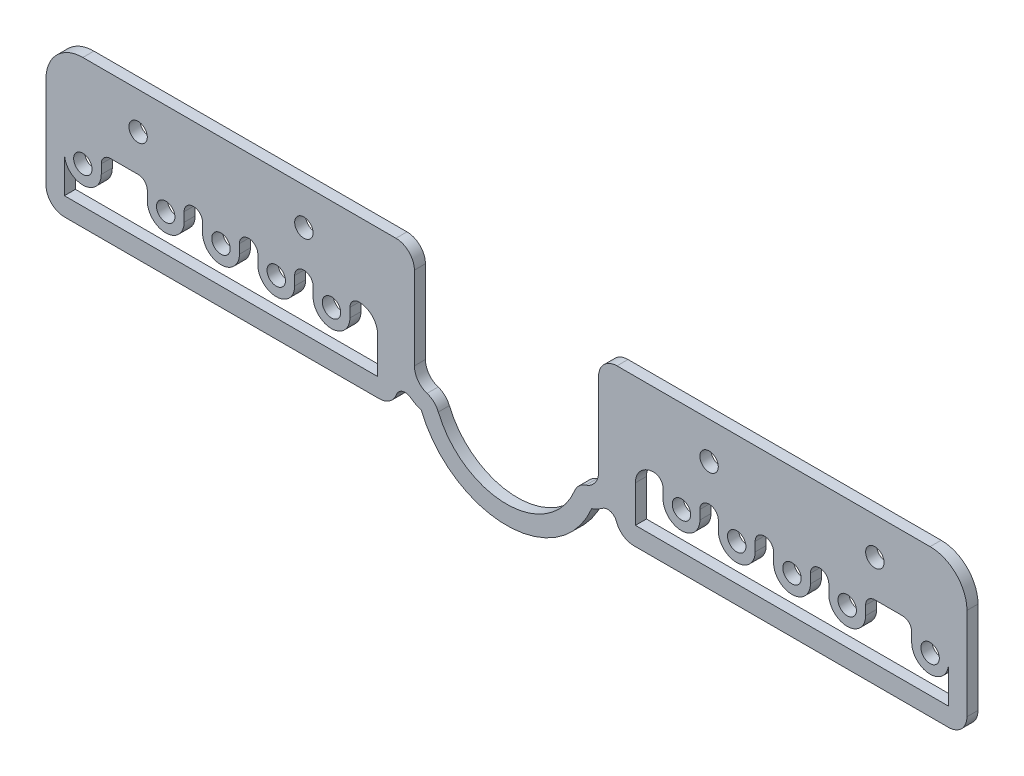
SolidWorks part; units mm, degrees
ref_plane "Front Plane" through (0, 0, 0) normal (0, 0, 1) x (1, 0, 0)
ref_plane "Top Plane" through (0, 0, 0) normal (0, 1, 0) x (1, 0, 0)
ref_plane "Right Plane" through (0, 0, 0) normal (1, 0, 0) x (0, 0, -1)
sketch "Sketch1" plane through (0, 0, 0) normal (0, 0, 1) x (1, 0, 0)
  line L0 (-40, 20) -> (-40, 55) construction
  line L4 (-250, -55) -> (-250, 3.1783)
  line L8 (-50, 75) -> (-230, 75) construction
  line L17 (0, -20) -> (0, -40)
  line L25 (0, -65) -> (0, -75)
  line L26 (0, 75) -> (0, -75) construction
  line L27 (-50, 95) -> (50, 95) construction
  line L34 (0, -75) -> (-230, -75)
  line L156 (-50, 75) -> (-230, 75) construction
  line L161 (0, -40) -> (0, -65)
  line L165 (-164.3309, 75) -> (-60, 75)
  line L167 (-230, 75) -> (-220, 75)
  line L171 (-250, 3.1783) -> (-250, 55)
  line L172 (-220, 75) -> (-164.3309, 75)
  line L173 (-50, 65) -> (-50, 20)
  arc A0 (-40, 20) -> (0, -20) centre (0, 20) ccw construction
  circle A1 centre (0, 20) radius 30 construction
  arc A4 (-230, -75) -> (-250, -55) centre (-230, -55) cw
  arc A5 (-250, 55) -> (-230, 75) centre (-230, 55) cw
  arc A124 (0, -20) -> (-37, 4.8013) centre (0, 20) cw
  arc A125 (-60, 75) -> (-50, 65) centre (-60, 65) cw
  arc A126 (-43.125, 10.5008) -> (-50, 20) centre (-40, 20) cw
  arc A127 (-37, 4.8013) -> (-43.125, 10.5008) centre (-46.25, 1.0016) ccw
  point P0 (0, 0)
  point P10 (-50, 10)
  point P11 (0, 50)
  point P30 (-40, 75)
  point P45 (0, -30)
  point P74 (0, 95)
  dimension "D3" = 80
  dimension "D4" = 60
  dimension "D6" = 55
  dimension "D7" = 75
  dimension "D10" = 10
  dimension "D11" = 20
  dimension "D8" = 10
  dimension "D5" = 10
  dimension "D9" = 20
  dimension "D13" = 210
  dimension "D16" = 100
  dimension "D17" = 20
  dimension "D26" = 250
extrude "Boss-Extrude1" add sketch "Sketch1" along normal blind 6
mirror "Mirror1" about plane through (0, -20, 6) normal (-1, 0, 0) of "Boss-Extrude1"
sketch "Sketch3" plane through (0, 0, 6) normal (0, 0, 1) x (1, 0, 0)
  line L3 (50, 20) -> (50, 65) construction
  line L4 (50, 20) -> (50, 65) construction
  line L7 (-60, 75) -> (-230, 75) construction
  line L8 (-250, 55) -> (-250, -55) construction
  line L9 (250, 55) -> (250, -55) construction
  circle A2 centre (110, 55) radius 5
  circle A3 centre (200, 55) radius 5
  circle A4 centre (-200, 55) radius 5
  circle A5 centre (-110, 55) radius 5
  dimension "D3" = 10
  dimension "D4" = 10
  dimension "D5" = 10
  dimension "D6" = 10
  dimension "D8" = 20
  dimension "D12" = 50
  dimension "D2" = 140
  dimension "D7" = 20
  dimension "D9" = 50
  dimension "D10" = 140
extrude "Cut-Extrude1" cut sketch "Sketch3" against normal through all contours A2 | A3 | A5 | A4
sketch "Sketch4" plane through (0, 0, 6) normal (0, 0, 1) x (1, 0, 0)
  line L0 (-230, -75) -> (230, -75) construction
  line L1 (-70, 25) -> (-70, -55)
  line L2 (-50, 20) -> (-50, 65) construction
  line L3 (-60, 75) -> (-230, 75) construction
  line L7 (-240, -55) -> (-240, 25)
  line L8 (-250, 55) -> (-250, -55) construction
  line L9 (-210, -65) -> (-190, -65)
  line L10 (-115, 25) -> (-115, 30)
  line L11 (-110, 35) -> (-80, 35)
  line L12 (-220, 25) -> (-220, 30)
  line L13 (-215, 35) -> (-140, 35)
  line L14 (-135, 30) -> (-135, 25)
  line L15 (-230, -65) -> (-210, -65)
  line L16 (-110, -65) -> (-90, -65)
  line L17 (0, 0) -> (0, -75) construction
  line L18 (-190, -65) -> (-110, -65)
  line L19 (90, -65) -> (80, -65)
  line L20 (190, -65) -> (110, -65)
  line L21 (-90, -65) -> (-80, -65)
  line L22 (110, -65) -> (90, -65)
  line L23 (230, -65) -> (210, -65)
  line L24 (230, 25) -> (125, 25) construction
  line L30 (221.3397, 20) -> (133.6603, 20)
  line L32 (110, 35) -> (80, 35)
  line L33 (115, 25) -> (115, 30)
  line L35 (210, -65) -> (190, -65)
  line L36 (240, -55) -> (240, 25)
  line L37 (70, 25) -> (70, -55)
  line L38 (125, 35) -> (230, 35)
  line L39 (230, 20) -> (125, 20) construction
  circle A0 centre (-230, 25) radius 5
  circle A3 centre (-125, 25) radius 5
  arc A6 (-230, -65) -> (-240, -55) centre (-230, -55) cw
  arc A8 (-222.2775, 18.6468) -> (-231.6408, 15.1355) centre (-230, 25) ccw
  arc A9 (-127.2754, 15.2623) -> (-127.1893, 15.2426) centre (-125, 25) ccw
  arc A12 (-110, 35) -> (-115, 30) centre (-110, 30) ccw
  arc A13 (-140, 35) -> (-135, 30) centre (-140, 30) cw
  arc A14 (-215, 35) -> (-220, 30) centre (-215, 30) ccw
  arc A15 (-70, -55) -> (-80, -65) centre (-80, -55) cw
  arc A16 (-70, 25) -> (-80, 35) centre (-80, 25) ccw
  arc A17 (-117.6445, 18.2253) -> (-134.5708, 22.1017) centre (-125, 25) ccw
  arc A19 (-231.6408, 15.1355) -> (-222.2775, 18.6468) centre (-230, 25) ccw
  arc A20 (-134.5708, 22.1017) -> (-117.3815, 18.5225) centre (-125, 25) ccw
  arc A21 (133.6603, 20) -> (117.3815, 18.5225) centre (125, 25) cw
  arc A22 (231.6408, 15.1355) -> (222.2775, 18.6468) centre (230, 25) cw
  arc A23 (117.6445, 18.2253) -> (125, 35) centre (125, 25) cw
  arc A24 (70, 25) -> (80, 35) centre (80, 25) cw
  arc A25 (70, -55) -> (80, -65) centre (80, -55) ccw
  arc A26 (230, 35) -> (231.6408, 15.1355) centre (230, 25) cw
  arc A28 (110, 35) -> (115, 30) centre (110, 30) cw
  arc A29 (127.2754, 15.2623) -> (127.1893, 15.2426) centre (125, 25) cw
  arc A30 (222.2775, 18.6468) -> (221.3397, 20) centre (230, 25) cw
  arc A31 (230, -65) -> (240, -55) centre (230, -55) ccw
  circle A32 centre (125, 25) radius 5
  circle A33 centre (230, 25) radius 5
  point P0 (0, -75)
  dimension "D1" = 10
  dimension "D13" = 10
  dimension "D14" = 20
  dimension "D10" = 5
  dimension "D15" = 5
  dimension "D17" = 10
  dimension "D2" = 230
  dimension "D4" = 5
  dimension "D5" = 125
  dimension "D8" = 50
  dimension "D9" = 10
  dimension "D11" = 20
  dimension "D12" = 80
  dimension "D16" = 80
extrude "Cut-Extrude2" cut sketch "Sketch4" against normal through all contours A20 A17 L14 A13 L13 A14 L12 A8 A19 L7 A6 L15 L9 L18 L16 L21 A15 L1 A16 L11 A12 L10 A9 | A0 | A3
sketch "Sketch8" plane through (0, 0, 6) normal (0, 0, 1) x (1, 0, 0)
  line L0 (-60, 0) -> (-60, -65)
  line L2 (-60, -65) -> (60, -65)
  line L3 (60, -65) -> (60, 0)
  line L4 (-230, -65) -> (-80, -65) construction
  arc A0 (43.125, 10.5008) -> (50, 20) centre (40, 20) ccw construction
  arc A1 (43.125, 10.5008) -> (37, 4.8013) centre (46.25, 1.0016) ccw construction
  arc A2 (-37, 4.8013) -> (-43.125, 10.5008) centre (-46.25, 1.0016) ccw construction
  arc A3 (-50, 20) -> (-43.125, 10.5008) centre (-40, 20) ccw construction
  arc A4 (-37, 4.8013) -> (37, 4.8013) centre (0, 20) ccw construction
  arc A5 (43.125, 10.5008) -> (50, 20) centre (40, 20) ccw construction
  arc A6 (43.125, 10.5008) -> (37, 4.8013) centre (46.25, 1.0016) ccw construction
  arc A7 (-37, 4.8013) -> (-43.125, 10.5008) centre (-46.25, 1.0016) ccw construction
  arc A8 (-50, 20) -> (-43.125, 10.5008) centre (-40, 20) ccw construction
  arc A9 (-37, 4.8013) -> (37, 4.8013) centre (0, 20) ccw construction
  arc A10 (-52, 4) -> (-46.25, 1.0016) centre (-40, 20) ccw
  arc A11 (-46.25, 1.0016) -> (-46.25, 1.0016) centre (-46.25, 1.0016) ccw
  arc A12 (-46.25, 1.0016) -> (46.25, 1.0016) centre (0, 20) ccw
  arc A13 (46.25, 1.0016) -> (46.25, 1.0016) centre (46.25, 1.0016) ccw
  arc A14 (46.25, 1.0016) -> (52, 4) centre (40, 20) ccw
  arc A15 (46.25, 1.0016) -> (60, 20) centre (40, 20) ccw construction
  arc A16 (60, 0) -> (52, 4) centre (55, 0) ccw
  arc A17 (-60, 20) -> (-46.25, 1.0016) centre (-40, 20) ccw construction
  arc A18 (-60, 0) -> (-52, 4) centre (-55, 0) cw
  dimension "D2" = 5
  dimension "D1" = 10
extrude "Cut-Extrude5" cut sketch "Sketch8" against normal through all
fillet "Fillet5" radius 5 1 edges at (-60, -65, 3)
fillet "Fillet6" radius 5 1 edges at (60, -65, 3)
mirror "Mirror2" about plane through (0, 0, 0) normal (1, 0, 0) of "Cut-Extrude2"
sketch "Sketch9" plane through (0, 0, 6) normal (0, 0, 1) x (1, 0, 0)
  line L0 (-250, 5) -> (-70, 5)
  line L1 (-250, 55) -> (-250, -55) construction
  line L2 (250, 55) -> (250, -55) construction
  line L3 (250, 5) -> (250, -5)
  line L4 (250, -5) -> (70, -5)
  line L5 (-250, -5) -> (-250, 5)
  line L6 (-215, 35) -> (-140, 35) construction
  line L7 (-70, 5) -> (-70, -5)
  line L8 (-70, 25) -> (-70, -55) construction
  line L9 (70, 5) -> (70, -5)
  line L10 (70, 25) -> (70, -55) construction
  line L11 (70, 5) -> (250, 5)
  line L12 (-70, -5) -> (-250, -5)
  dimension "D1" = 10
  dimension "D2" = 30
extrude "Boss-Extrude2" add sketch "Sketch9" against normal up to surface (6 mm away) up to face at (225, 25, 0)
sketch "Sketch10" plane through (0, 0, 6) normal (0, 0, 1) x (1, 0, 0)
  line L0 (-240, -5) -> (-250, -5)
  line L1 (-250, 55) -> (-250, -55) construction
  line L2 (-250, -5) -> (-250, -80.0757)
  line L3 (-250, -80.0757) -> (258.5235, -80.0757)
  line L4 (258.5235, -80.0757) -> (258.5235, -5)
  line L5 (258.5235, -5) -> (43.3013, -5)
  line L7 (-43.3013, -5) -> (-240, -5)
  arc A0 (-46.25, 1.0016) -> (46.25, 1.0016) centre (0, 20) ccw construction
  arc A1 (-43.3013, -5) -> (43.3013, -5) centre (0, 20) ccw
  point P15 (0, 0)
extrude "Cut-Extrude6" cut sketch "Sketch10" against normal through all
fillet "Fillet7" radius 10 4 edges at (-60, -5, 3) (250, -5, 3) (60, -5, 3) (-250, -5, 3)
sketch "Sketch11" plane through (0, 0, 6) normal (0, 0, 1) x (1, 0, 0)
  line L0 (-115, 25) -> (-115, 30) construction
  line L1 (-135, 30) -> (-135, 25) construction
  line L2 (-115, 25) -> (-115, 30)
  line L3 (-135, 30) -> (-135, 25)
  line L4 (-85, 25) -> (-85, 30)
  line L5 (-105, 30) -> (-105, 25)
  line L6 (-145, 25) -> (-145, 30)
  line L7 (-165, 30) -> (-165, 25)
  line L8 (-175, 25) -> (-175, 30)
  line L9 (-195, 30) -> (-195, 25)
  line L10 (-200, 35) -> (-200, 37.8019)
  line L11 (-200, 37.8019) -> (-80, 37.8019)
  line L12 (-80, 37.8019) -> (-80, 35)
  arc A0 (-110, 35) -> (-115, 30) centre (-110, 30) ccw construction
  circle A1 centre (-125, 25) radius 5 construction
  arc A2 (-135, 25) -> (-115, 25) centre (-125, 25) ccw construction
  arc A3 (-135, 30) -> (-140, 35) centre (-140, 30) ccw construction
  arc A4 (-110, 35) -> (-115, 30) centre (-110, 30) ccw
  circle A5 centre (-125, 25) radius 5
  arc A6 (-135, 25) -> (-115, 25) centre (-125, 25) ccw
  arc A7 (-135, 30) -> (-140, 35) centre (-140, 30) ccw
  arc A8 (-80, 35) -> (-85, 30) centre (-80, 30) ccw
  circle A9 centre (-95, 25) radius 5
  arc A10 (-105, 25) -> (-85, 25) centre (-95, 25) ccw
  arc A11 (-105, 30) -> (-110, 35) centre (-110, 30) ccw
  arc A12 (-140, 35) -> (-145, 30) centre (-140, 30) ccw
  circle A13 centre (-155, 25) radius 5
  arc A14 (-165, 25) -> (-145, 25) centre (-155, 25) ccw
  arc A15 (-165, 30) -> (-170, 35) centre (-170, 30) ccw
  arc A16 (-170, 35) -> (-175, 30) centre (-170, 30) ccw
  circle A17 centre (-185, 25) radius 5
  arc A18 (-195, 25) -> (-175, 25) centre (-185, 25) ccw
  arc A19 (-195, 30) -> (-200, 35) centre (-200, 30) ccw
  dimension "D1" = 2
  dimension "D2" = 3
extrude "Boss-Extrude3" add sketch "Sketch11" against normal up to surface (6 mm away) contours A19 L9 A18 L8 A16 A15 L7 A14 L6 A12 A7 L3 A6 L2 A4 A11 L5 A10 L4 A8 L12 L11 L10 A17 A13 A9 A5 up to face at (0, 21.7684, 0)
mirror "Mirror3" about plane through (0, 0, 0) normal (1, 0, 0) of "Boss-Extrude3"
